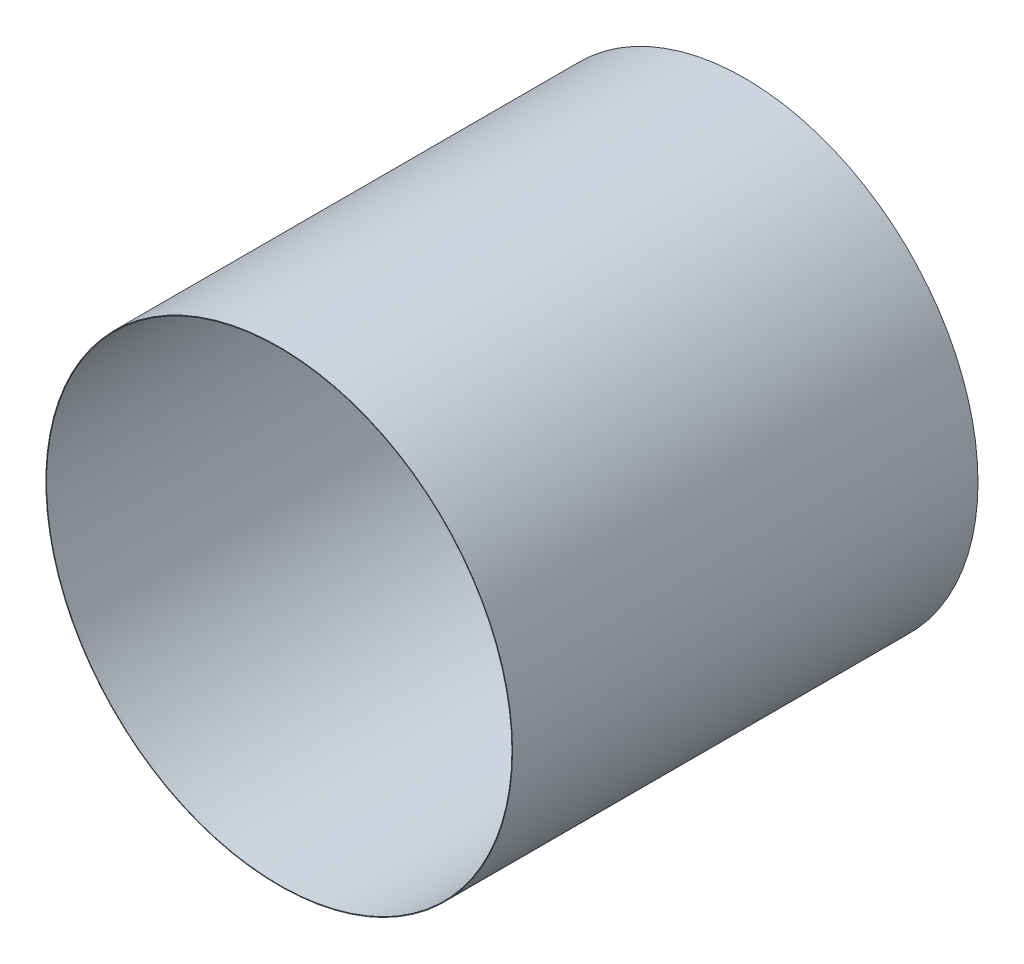
SolidWorks part; units mm, degrees
ref_plane "Ebene vorne" through (0, 0, 0) normal (0, 0, 1) x (1, 0, 0)
ref_plane "Ebene oben" through (0, 0, 0) normal (0, 1, 0) x (1, 0, 0)
ref_plane "Ebene rechts" through (0, 0, 0) normal (1, 0, 0) x (0, 0, -1)
sketch "Sketch1" plane through (0, 0, 0) normal (0, 0, 1) x (1, 0, 0)
  circle A0 centre (0, 0) radius 75
  circle A1 centre (0, 0) radius 75.2
  dimension "D1" = 0.2
  dimension "D2" = 150
extrude "Boss-Extrude1" add sketch "Sketch1" along normal blind 150
